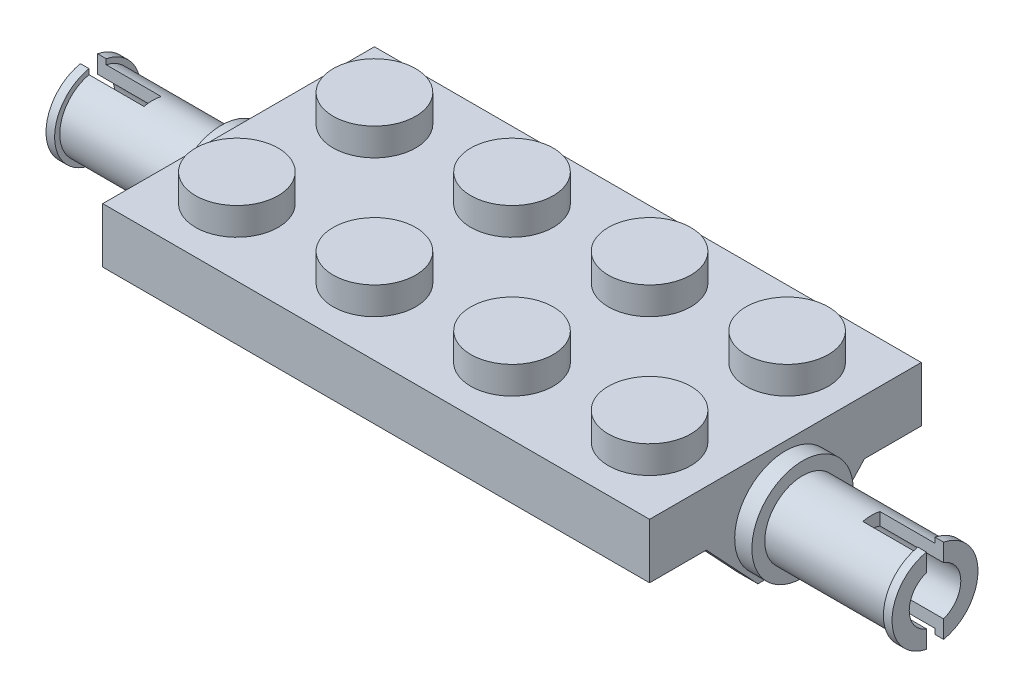
SolidWorks part; units mm, degrees
material "ABS"
ref_plane "Front Plane" through (0, 0, 0) normal (0, 0, 1) x (1, 0, 0)
ref_plane "Top Plane" through (0, 0, 0) normal (0, 1, 0) x (1, 0, 0)
ref_plane "Right Plane" through (0, 0, 0) normal (1, 0, 0) x (0, 0, -1)
sketch "Sketch1" plane through (0, 0, 0) normal (0, 0, 1) x (1, 0, 0)
  line L1 (0, 0) -> (31.8, 0)
  line L2 (0, 0) -> (0, 3.2)
  line L3 (0, 3.2) -> (31.8, 3.2)
  line L4 (31.8, 0) -> (31.8, 3.2)
  dimension "D1" = 3.2
  dimension "D2" = 31.8
extrude "Boss-Extrude1" add sketch "Sketch1" against normal blind 15.8
sketch "Sketch2" plane through (0, 3.2, 0) normal (0, 1, 0) x (1, 0, 0)
  line L0 (0, 15.8) -> (0, 0) construction
  line L1 (31.8, 0) -> (0, 0) construction
  circle A0 centre (3.9, 3.9) radius 2.4
  dimension "D1" = 4.8
  dimension "D2" = 3.9
  dimension "D3" = 3.9
extrude "Boss-Extrude2" add sketch "Sketch2" along normal blind 1.6 contours A0
pattern_linear "LPattern1" count 2 spacing 8 along (0, 0, -1) count 6 spacing 8 along (1, 0, 0) of "Boss-Extrude2"
shell "Shell1" thickness 1.2
sketch "Sketch3" plane through (0, 2, 0) normal (0, -1, 0) x (1, 0, 0)
  line L0 (0, -15.8) -> (0, 0) construction
  line L1 (0, -15.8) -> (31.8, -15.8) construction
  circle A0 centre (15.9, -7.9) radius 3.25
  circle A1 centre (15.9, -7.9) radius 2.4
  dimension "D1" = 4.8
  dimension "D2" = 6.5
  dimension "D3" = 15.9
  dimension "D4" = 7.9
extrude "Boss-Extrude3" add sketch "Sketch3" along normal offset from surface (1.8 mm away) 0.2 up to face at (15.9, 0, -7.9)
sketch "Sketch4" plane through (0, 2, 0) normal (0, -1, 0) x (1, 0, 0)
  line L0 (30.6, -1.2) -> (1.2, -1.2) construction
  line L1 (30.6, -1.2) -> (1.2, -1.2) construction
  line L2 (15.9, -1.2) -> (9.5, -1.2) construction
  line L3 (15.9, -1.2) -> (22.3, -1.2) construction
  line L4 (9.5, -1.2) -> (9.5, -14.6)
  line L5 (30.6, -14.6) -> (1.2, -14.6) construction
  line L6 (22.3, -1.2) -> (22.3, -14.6)
  line L7 (9.5, -1.2) -> (8.7, -1.2)
  line L8 (8.7, -1.2) -> (8.7, -14.6)
  line L9 (8.7, -14.6) -> (9.5, -14.6)
  line L10 (22.3, -1.2) -> (23.1, -1.2)
  line L11 (23.1, -1.2) -> (23.1, -14.6)
  line L12 (23.1, -14.6) -> (22.3, -14.6)
  dimension "D1" = 6.4
  dimension "D2" = 6.4
  dimension "D3" = 0.8
  dimension "D4" = 0.8
extrude "Boss-Extrude4" add sketch "Sketch4" along normal offset from surface (1.8 mm away) 0.2 up to face at (15.9, 0, -7.9)
ref_plane "Plane1" through (15.9, 0, 0) normal (-1, 0, 0) x (0, 0, 1)
sketch "Sketch5" plane through (31.8, 0, 0) normal (1, 0, 0) x (0, 0, -1)
  line L0 (0, 0) -> (3.3, 0) construction
  line L1 (15.8, 0) -> (0, 0) construction
  line L2 (15.8, 0) -> (12.5, 0) construction
  line L3 (6.3, -3.2) -> (9.5, -3.2)
  line L4 (0, 3.2) -> (0, 0)
  line L5 (0, 0) -> (15.8, 0)
  line L6 (15.8, 0) -> (15.8, 3.2)
  line L7 (15.8, 3.2) -> (0, 3.2)
  line L8 (0, 3.2) -> (0, 0) construction
  line L10 (15.8, 0) -> (15.8, 3.2) construction
  line L11 (15.8, 3.2) -> (0, 3.2) construction
  line L12 (3.3, 0) -> (6.3, -3.2)
  line L13 (12.5, 0) -> (9.5, -3.2)
  line L14 (3.3, 0) -> (12.5, 0)
  point P10 (7.9, 0)
  point P11 (7.9, -3.2)
  dimension "D2" = 9.2
  dimension "D3" = 3.2
  dimension "D4" = 3.2
  dimension "D1" = 0
extrude "Boss-Extrude5" add sketch "Sketch5" against normal blind 1.2
mirror "Mirror1" about plane through (15.9, 0, 0) normal (-1, 0, 0) of "Boss-Extrude5"
sketch "Sketch7" plane through (31.8, 0, 0) normal (1, 0, 0) x (0, 0, -1)
  line L0 (6.3, -3.2) -> (9.5, -3.2) construction
  line L1 (6.3, -3.2) -> (9.5, -3.2) construction
  line L2 (15.8, 3.2) -> (0, 3.2) construction
  line L3 (15.8, 3.2) -> (0, 3.2) construction
  circle A0 centre (7.9, -0.25) radius 2.95
  point P7 (7.9, 3.2)
  dimension "D1" = 5.9
extrude "Boss-Extrude6" add sketch "Sketch7" along normal blind 1
sketch "Sketch8" plane through (32.8, 0, 0) normal (1, 0, 0) x (0, 0, -1)
  circle A0 centre (7.9, -0.25) radius 2.2
  circle A1 centre (7.9, -0.25) radius 2.95
  circle A2 centre (7.9, -0.25) radius 2.95 construction
  circle A3 centre (7.9, -0.25) radius 1.5
  dimension "D2" = 4.4
  dimension "D3" = 0.7
  dimension "D1" = 0
extrude "Boss-Extrude7" add sketch "Sketch8" along normal blind 7.7
sketch "Sketch9" plane through (40.5, 0, 0) normal (1, 0, 0) x (0, 0, -1)
  circle A0 centre (7.9, -0.25) radius 2.5
  circle A1 centre (7.9, -0.25) radius 2.2
  circle A2 centre (7.9, -0.25) radius 2.2
  dimension "D2" = 5
  dimension "D1" = 0
extrude "Boss-Extrude8" add sketch "Sketch9" against normal blind 0.5
sketch "Sketch10" plane through (40.5, 0, 0) normal (1, 0, 0) x (0, 0, -1)
  line L0 (7.9, -3.2) -> (7.9, 2.7)
  line L1 (7.9, 2.7) -> (7.4, 2.7)
  line L2 (7.9, 2.7) -> (8.4, 2.7)
  line L3 (7.9, -3.2) -> (7.4, -3.2)
  line L4 (7.9, -3.2) -> (8.4, -3.2)
  line L5 (7.4, 2.7) -> (7.4, -3.2)
  line L6 (8.4, 2.7) -> (8.4, -3.2)
  circle A0 centre (7.9, -0.25) radius 2.95 construction
  circle A1 centre (7.9, -0.25) radius 2.5
  circle A2 centre (7.9, -0.25) radius 2.5 construction
  circle A3 centre (7.9, -0.25) radius 2.95 construction
  circle M6 centre (7.9, -0.25) radius 1.5
  circle M7 centre (7.9, -0.25) radius 2.5
  dimension "D2" = 0.5
  dimension "D3" = 0.5
  dimension "D1" = 0
extrude "Cut-Extrude1" cut sketch "Sketch10" against normal blind 3.7 contours L6 L0 M7 M6 | L5 L0 M7 M6 | L5 L0 M6 M7 | L6 L0 M6 M7
mirror "Mirror2" about plane through (15.9, 0, 0) normal (-1, 0, 0) of "Cut-Extrude1", "Boss-Extrude7", "Boss-Extrude8", "Boss-Extrude6"
